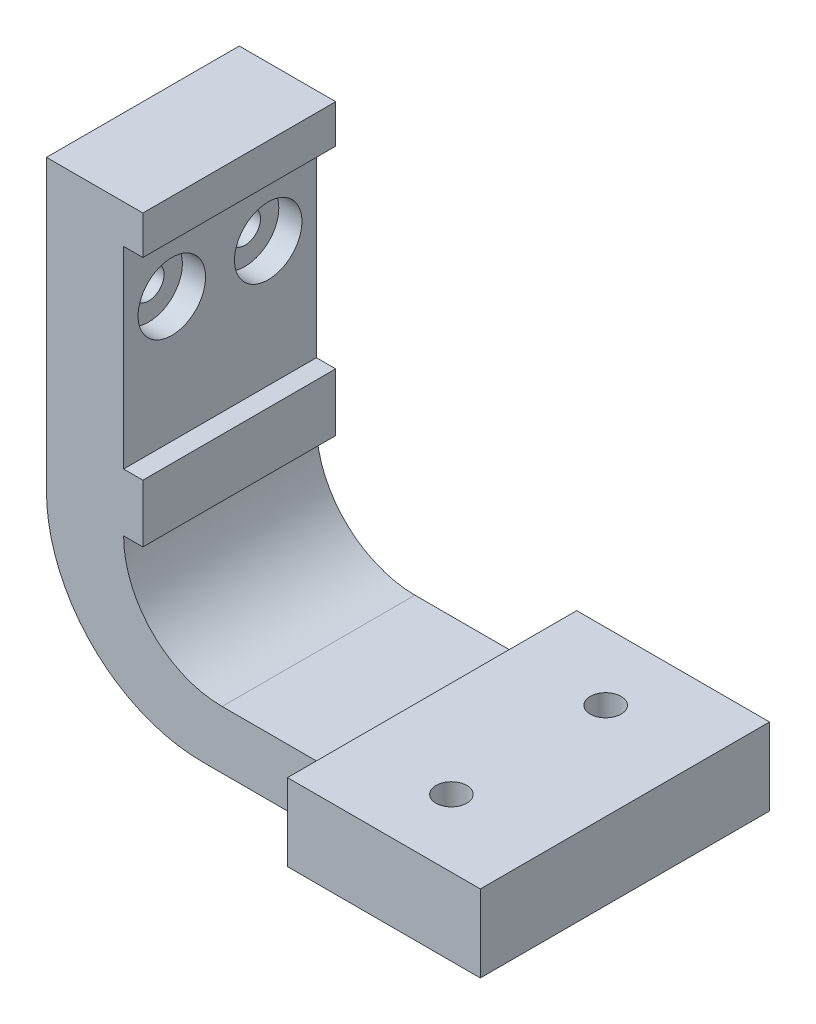
SolidWorks part; units mm, degrees
material "6061-T6 (SS)"
ref_plane "Front Plane" through (0, 0, 0) normal (0, 0, 1) x (1, 0, 0)
ref_plane "Top Plane" through (0, 0, 0) normal (0, 1, 0) x (1, 0, 0)
ref_plane "Right Plane" through (0, 0, 0) normal (1, 0, 0) x (0, 0, -1)
sketch "Sketch1" plane through (0, 0, 0) normal (0, 0, 1) x (1, 0, 0)
  line L0 (-15.4886, 8) -> (-17.5374, 8) construction
  line L9 (-17.5374, 3) -> (-17.5374, 13)
  line L10 (-21.5374, 0) -> (-21.5374, 15)
  line L11 (-21.5374, 15) -> (-16.5374, 15)
  line L12 (-16.5374, 15) -> (-16.5374, 13)
  line L13 (-16.5374, 0) -> (-17.5374, 0)
  line L17 (-12.4274, -5.11) -> (3.4626, -5.11)
  line L18 (3.4626, -5.11) -> (3.4626, -8.11)
  line L19 (3.4626, -8.11) -> (-13.4274, -8.11)
  line L20 (-17.5374, 13) -> (-16.5374, 13)
  line L21 (-17.5374, 3) -> (-16.5374, 3)
  line L22 (-16.5374, 3) -> (-16.5374, 0)
  line L23 (-21.5374, 0) -> (-21.5374, -8.11) construction
  line L24 (-21.5374, -8.11) -> (-19.9521, -8.11) construction
  line L25 (-13.4274, -8.11) -> (-13.4274, 0) construction
  line L26 (-17.5374, 0) -> (-17.5374, -5.11) construction
  line L27 (-17.5374, -5.11) -> (-13.4274, -5.11) construction
  line L29 (-12.4274, -5.11) -> (-10.0144, -5.11) construction
  arc A4 (-21.5374, 0) -> (-13.4274, -8.11) centre (-13.4274, 0) ccw
  arc A5 (-17.5374, 0) -> (-12.4274, -5.11) centre (-12.4274, 0) ccw
  point P15 (-17.5374, 8)
  point P21 (-12.4274, 0)
  dimension "D3" = 8.11
  dimension "D4" = 3
  dimension "D1" = 15
  dimension "D2" = 5
  dimension "D5" = 25
  dimension "D6" = 10
  dimension "D7" = 2
  dimension "D8" = 1
  dimension "D9" = 0
  dimension "D10" = 3
  dimension "D12" = 8.11
  dimension "D13" = 8.11
  dimension "D14" = 5.11
  dimension "D15" = 5.11
extrude "Boss-Extrude1" add sketch "Sketch1" along normal mid plane 10
sketch "Sketch2" plane through (-17.5374, 0, 0) normal (1, 0, 0) x (0, 0, -1)
  line L0 (-5, 8) -> (5, 8) construction
  line L1 (-5, 3) -> (-5, 13) construction
  line L2 (5, 3) -> (5, 13) construction
  line L3 (-5, 9.5) -> (5, 9.5) construction
  line L4 (0, 9.5) -> (0, 8) construction
  point P8 (-2.5, 9.5)
  point P11 (2.5, 9.5)
  dimension "D2" = 2.5
  dimension "D1" = 1.5
hole_wizard "Tap Drill for M2x0.4 Tap1" positions "3DSketch1" profile "Sketch3" hole size "M2x0.4" standard "ANSI Metric" end condition through all
sketch3d "3DSketch1"
  point P0 (-17.5374, 9.5, 2.5)
  point P3 (-17.5374, 9.5, -2.5)
sketch "Sketch3" plane through (-17.5374, 9.5, 2.5) normal (0, 1, 0) x (0, 0, -1)
  line L0 (0, 0) -> (0, 4)
  line L1 (0, 4) -> (0.8, 4)
  line L2 (0.8, 4) -> (0.8, 0)
  line L5 (0.8, 0) -> (0, 0)
  line L11 (0, -6.35) -> (0, 107.95) construction
  dimension "Thru Hole Dia." = 1.6
  dimension "Thru Hole Depth" = 4
sketch "Sketch4" plane through (-17.5374, 0, 0) normal (1, 0, 0) x (0, 0, -1)
  circle A0 centre (-2.5, 9.5) radius 1.75
  circle A1 centre (2.5, 9.5) radius 1.75
  dimension "D1" = 3.5
  dimension "D2" = 3.5
extrude "Cut-Extrude1" cut sketch "Sketch4" against normal blind 1.2
sketch "Sketch5" plane through (0, -8.11, 0) normal (0, -1, 0) x (1, 0, 0)
  line L0 (3.4626, -7.5) -> (3.4626, 7.5)
  line L1 (3.4626, 5) -> (3.4626, -5) construction
  line L2 (3.4626, 7.5) -> (-6.5374, 7.5)
  line L3 (-6.5374, 7.5) -> (-6.5374, -7.5)
  line L4 (-6.5374, -7.5) -> (3.4626, -7.5)
  point P3 (3.4626, 0)
  dimension "D1" = 10
  dimension "D2" = 15
extrude "Boss-Extrude2" add sketch "Sketch5" against normal blind 4
sketch "Sketch6" plane through (0, -4.11, 0) normal (0, 1, 0) x (1, 0, 0)
  line L0 (3.4626, 0) -> (-6.5374, 0) construction
  line L1 (3.4626, 7.5) -> (3.4626, -7.5) construction
  line L2 (-6.5374, -7.5) -> (-6.5374, 7.5) construction
  line L3 (-1.5374, -7.5) -> (-1.5374, 7.5) construction
  line L4 (3.4626, -7.5) -> (-6.5374, -7.5) construction
  line L5 (-6.5374, 7.5) -> (3.4626, 7.5) construction
  point P12 (-1.5374, -4)
  point P13 (-1.5374, 0)
  point P14 (-1.5374, 4)
  dimension "D1" = 4
hole_wizard "Tap Drill for M2x0.4 Tap2" positions "3DSketch2" profile "Sketch7" hole size "M2x0.4" standard "ANSI Metric" end condition through all
sketch3d "3DSketch2"
  point P0 (-1.5374, -4.11, 4)
  point P3 (-1.5374, -4.11, -4)
sketch "Sketch7" plane through (-1.5374, -4.11, 4) normal (1, 0, 0) x (0, 0, 1)
  line L0 (0, 0) -> (0, 4)
  line L1 (0, 4) -> (0.8, 4)
  line L2 (0.8, 4) -> (0.8, 0)
  line L5 (0.8, 0) -> (0, 0)
  line L11 (0, -6.35) -> (0, 107.95) construction
  dimension "Thru Hole Dia." = 1.6
  dimension "Thru Hole Depth" = 4
